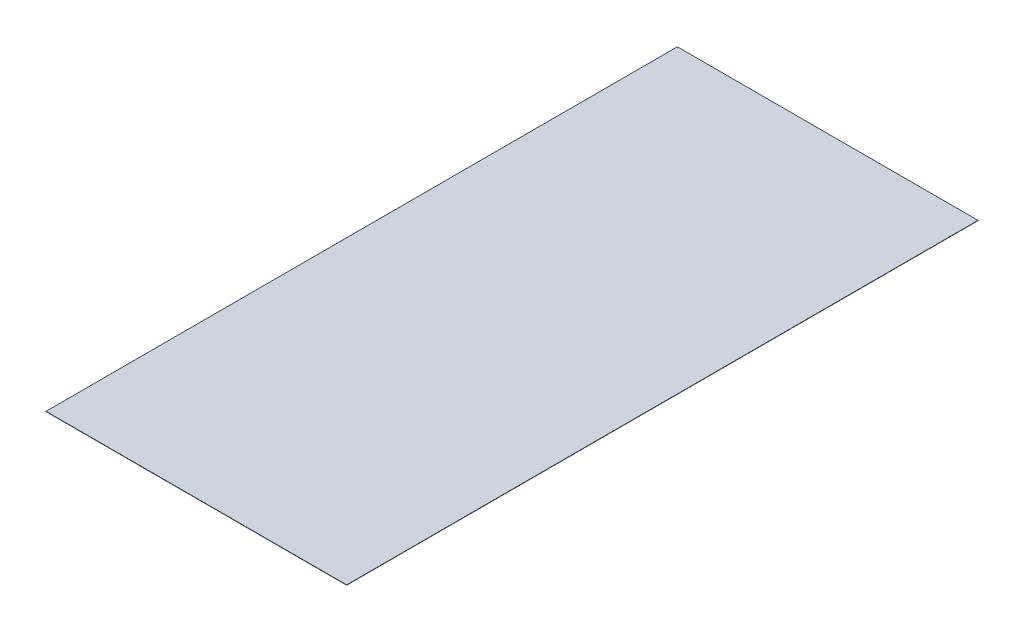
SolidWorks part; units mm, degrees
ref_plane "Спереди" through (0, 0, 0) normal (0, 0, 1) x (1, 0, 0)
ref_plane "Сверху" through (0, 0, 0) normal (0, 1, 0) x (1, 0, 0)
ref_plane "Справа" through (0, 0, 0) normal (1, 0, 0) x (0, 0, -1)
other "Configuration Table"
sketch "Эскиз1" plane through (0, 0, 0) normal (0, 1, 0) x (1, 0, 0)
  line L1 (500, 1050) -> (-500, 1050)
  line L2 (500, 1050) -> (500, -1050)
  line L3 (500, -1050) -> (-500, -1050)
  line L4 (-500, 1050) -> (-500, -1050)
  line L5 (500, 1050) -> (-500, -1050) construction
  line L6 (500, -1050) -> (-500, 1050) construction
  point P0 (0, 0)
extrude "Бобышка-Вытянуть1" add sketch "Эскиз1" along normal blind 1
